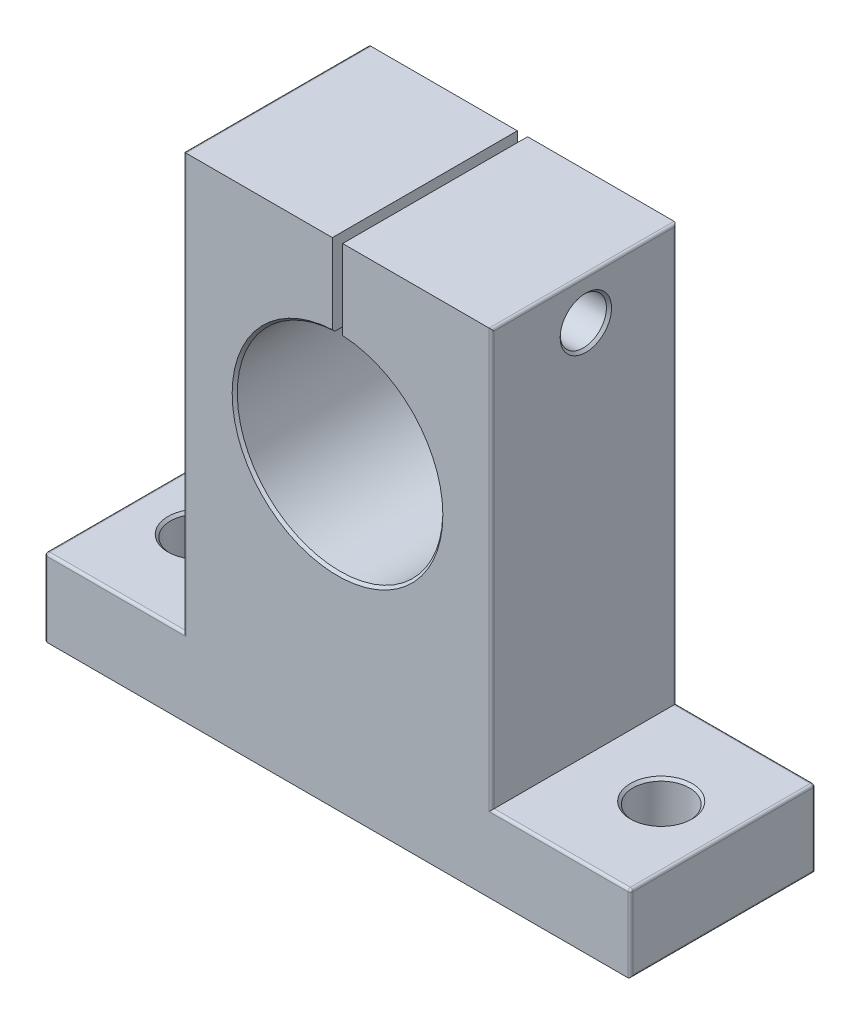
SolidWorks part; units mm, degrees
material "1060 Alloy"
ref_plane "Front Plane" through (0, 0, 0) normal (0, 0, 1) x (1, 0, 0)
ref_plane "Top Plane" through (0, 0, 0) normal (0, 1, 0) x (1, 0, 0)
ref_plane "Right Plane" through (0, 0, 0) normal (1, 0, 0) x (0, 0, -1)
sketch "Sketch1" plane through (0, 0, 0) normal (0, 0, 1) x (1, 0, 0)
  line L0 (0, 0) -> (-50000, 0) construction
  line L1 (0, 0) -> (0, 50000) construction
  line L2 (-57, -7.5) -> (-57, 7.5)
  line L3 (-57, 7.5) -> (-30, 7.5)
  line L4 (-30, 7.5) -> (-30, 88.5)
  line L5 (-30, 88.5) -> (-1, 88.5)
  line L6 (30, 88.5) -> (30, 7.5)
  line L7 (30, 7.5) -> (57, 7.5)
  line L8 (57, 7.5) -> (57, -7.5)
  line L9 (57, -7.5) -> (-57, -7.5)
  line L10 (45, -3) -> (45, 3) construction
  line L11 (-45, -3) -> (-45, 3) construction
  line L12 (-1, 88.5) -> (-1, 72.475)
  line L13 (1, 88.5) -> (1, 72.475)
  line L14 (1, 88.5) -> (30, 88.5)
  arc A0 (-1, 72.475) -> (1, 72.475) centre (0, 52.5) ccw
  point P8 (-57, 0)
  point P10 (24, -4)
  point P15 (0, -7.5)
  point P17 (0, 0)
  point P21 (45, 0)
  dimension "Shaft Diameter" = 40
  dimension "W" = 114
  dimension "P" = 60
  dimension "F" = 96
  dimension "G" = 15
  dimension "B" = 90
  dimension "D1" = 2
  dimension "h" = 60
extrude "Boss-Extrude1" add sketch "Sketch1" along normal mid plane 36
sketch "Sketch2" plane through (0, 7.5, 0) normal (0, 1, 0) x (1, 0, 0)
  line L0 (0, 0) -> (50000, 0) construction
  line L1 (0.3141, 0) -> (-49999.6859, 0) construction
  line L2 (0, 2.4842) -> (0, 50002.4842) construction
  circle A0 centre (45, 0) radius 5.5
  circle A1 centre (-45, 0) radius 5.5
  point P11 (17.1569, 0)
  dimension "B" = 90
  dimension "S" = 11
extrude "Cut-Extrude1" cut sketch "Sketch2" against normal through all
sketch "Sketch5" plane through (-1, 0, 0) normal (1, 0, 0) x (0, 0, -1)
  line L0 (-18, 80.4875) -> (18, 80.4875) construction
  line L1 (18, 72.475) -> (18, 88.5) construction
  line L2 (0, 88.5) -> (0, 72.475) construction
  line L3 (-18, 88.5) -> (18, 88.5) construction
  line L4 (-18, 72.475) -> (18, 72.475) construction
  line L5 (-18, 72.475) -> (-18, 88.5) construction
  circle A0 centre (0.3307, 80.4875) radius 4.5
  dimension "Clamping bold" = 9
extrude "Cut-Extrude2" cut sketch "Sketch5" against normal through all both and the other way through all
chamfer "Chamfer2" distance 0.5 angle 45 6 edges at (0, 32.5, -18) (0, 32.5, 18) (-30, 80.4875, -4.8307) (-39.5, 7.5, 0) (30, 80.4875, 4.1693) (39.5, 7.5, 0)
fillet "Fillet2" radius 0.5 18 edges at (57, -7.5, 0) (57, 0, 18) (57, 7.5, 0) (57, 0, -18) (-57, 7.5, 0) (-57, 0, 18) (-57, -7.5, 0) (-57, 0, -18) (-43.5, 7.5, -18) (-43.5, 7.5, 18) (-30, 48, 18) (-30, 88.5, 0) (-30, 48, -18) (30, 48, -18) (30, 48, 18) (43.5, 7.5, 18) (43.5, 7.5, -18) (30, 88.5, 0)
equation "\"W\"= \"W@Sketch1\"'Width"
equation "\"B\"= \"B@Sketch1\"'between hold"
equation "\"F\"= \"F@Sketch1\"'Hight"
equation "\"P\"= \"P@Sketch1\""
equation "\"G\"= \"G@Sketch1\""
equation "\"Shaft diameter\"= \"Shaft Diameter@Sketch1\""
equation "\"S\" = \"S@Sketch2\"'M10"
equation "\"Clamping bold\" = 9'M8"
equation "\"h\"= \"h@Sketch1\""
